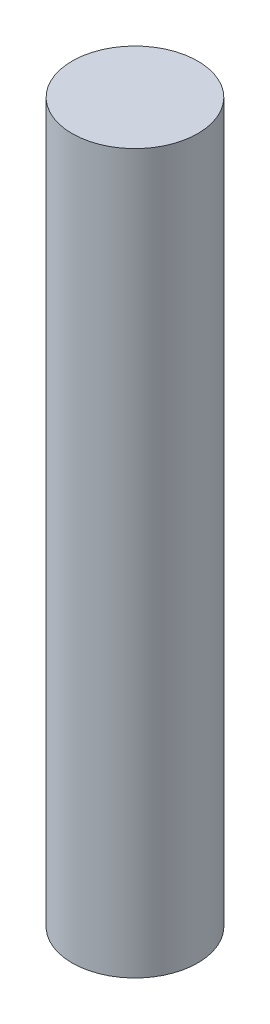
SolidWorks part; units mm, degrees
ref_plane "Front Plane" through (0, 0, 0) normal (0, 0, 1) x (1, 0, 0)
ref_plane "Top Plane" through (0, 0, 0) normal (0, 1, 0) x (1, 0, 0)
ref_plane "Right Plane" through (0, 0, 0) normal (1, 0, 0) x (0, 0, -1)
sketch "Sketch1" plane through (0, 0, 0) normal (0, 1, 0) x (1, 0, 0)
  circle A0 centre (0, 0) radius 1.75
  dimension "D1" = 3.5
extrude "Boss-Extrude1" add sketch "Sketch1" along normal blind 20
